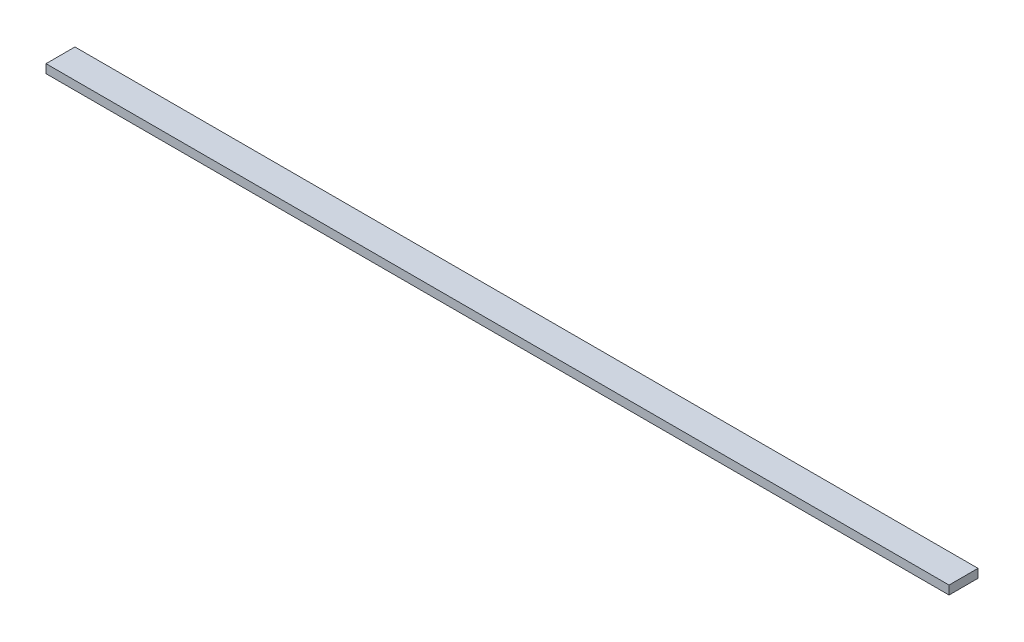
SolidWorks part; units mm, degrees
ref_plane "前视基准面" through (0, 0, 0) normal (0, 0, 1) x (1, 0, 0)
ref_plane "上视基准面" through (0, 0, 0) normal (0, 1, 0) x (1, 0, 0)
ref_plane "右视基准面" through (0, 0, 0) normal (1, 0, 0) x (0, 0, -1)
sketch "草图1" plane through (0, 0, 0) normal (0, 1, 0) x (1, 0, 0)
  line L1 (-407.4996, 218.5822) -> (1464.5004, 218.5822)
  line L2 (-407.4996, 218.5822) -> (-407.4996, 158.5822)
  line L3 (-407.4996, 158.5822) -> (1464.5004, 158.5822)
  line L4 (1464.5004, 218.5822) -> (1464.5004, 158.5822)
  dimension "D1" = 1872
  dimension "D2" = 60
extrude "凸台-拉伸1" add sketch "草图1" along normal blind 18
